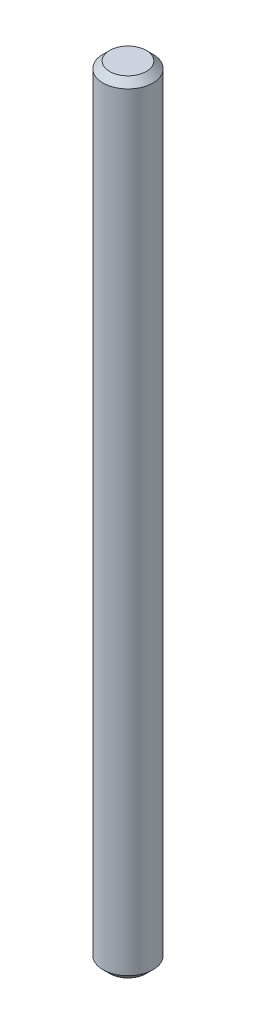
SolidWorks part; units mm, degrees
material "1.0038 (S235JRG2)"
ref_plane "Horní rovina" through (0, 0, 0) normal (0, 0, 1) x (1, 0, 0)
ref_plane "Přední rovina" through (0, 0, 0) normal (0, 1, 0) x (1, 0, 0)
ref_plane "Pravá rovina" through (0, 0, 0) normal (1, 0, 0) x (0, 0, -1)
sketch "Skica1" plane through (0, 0, 0) normal (0, 1, 0) x (1, 0, 0)
  circle A0 centre (0, 0) radius 0.75
  dimension "D1" = 1.5
extrude "Přidat vysunutím1" add sketch "Skica1" along normal blind 23.5
chamfer "Zkosení1" distance 0.2 angle 45 2 edges at (0, 23.5, 0.75) (0, 0, 0.75)
